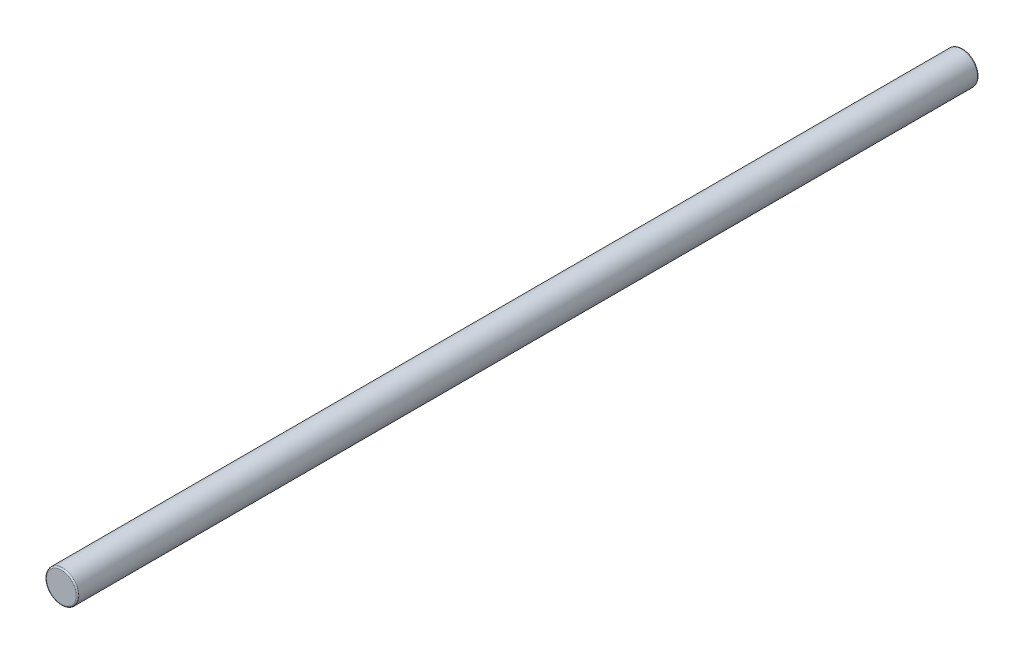
SolidWorks part; units mm, degrees
material "AISI 1020"
ref_plane "Alzado" through (0, 0, 0) normal (0, 0, 1) x (1, 0, 0)
ref_plane "Planta" through (0, 0, 0) normal (0, 1, 0) x (1, 0, 0)
ref_plane "Vista lateral" through (0, 0, 0) normal (1, 0, 0) x (0, 0, -1)
sketch "Croquis1" plane through (0, 0, 0) normal (0, 0, 1) x (1, 0, 0)
  circle A0 centre (0, 0) radius 6
  dimension "D1" = 12
extrude "Saliente-Extruir1" add sketch "Croquis1" along normal blind 335
fillet "Redondeo1" radius 0.5 2 edges at (6, 0, 0) (6, 0, 335)
